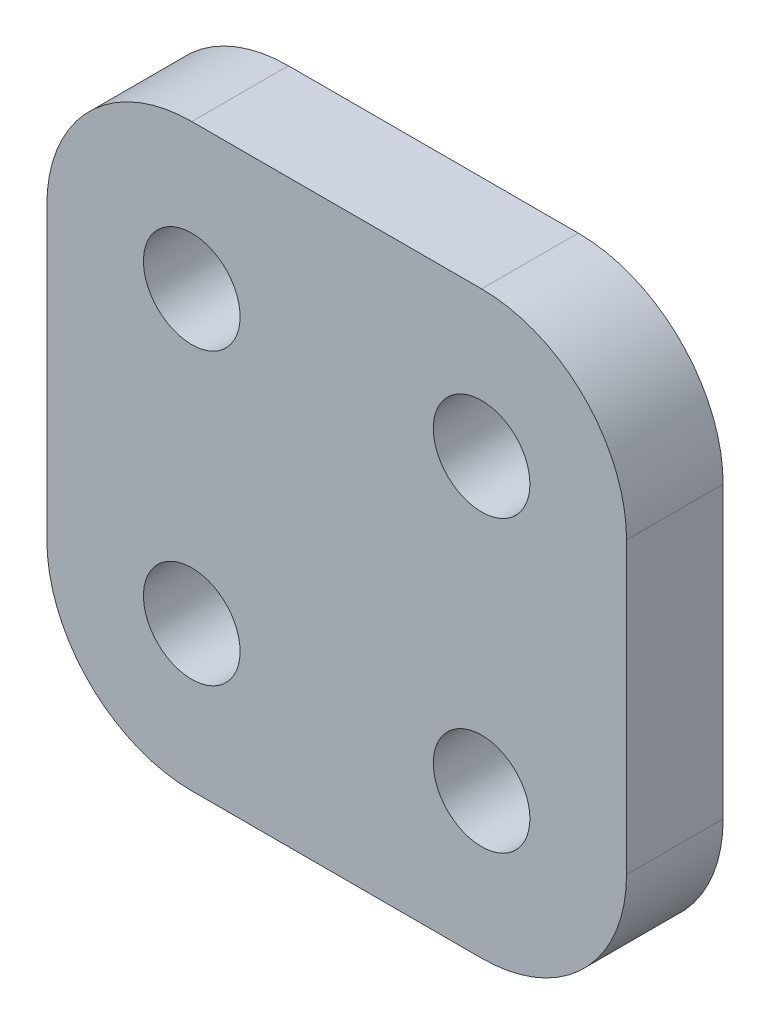
SolidWorks part; units mm, degrees
ref_plane "Alzado" through (0, 0, 0) normal (0, 0, 1) x (1, 0, 0)
ref_plane "Planta" through (0, 0, 0) normal (0, 1, 0) x (1, 0, 0)
ref_plane "Vista lateral" through (0, 0, 0) normal (1, 0, 0) x (0, 0, -1)
sketch "Model" plane through (0, 0, 0) normal (0, 0, 1) x (1, 0, 0)
  line L0 (195.3359, 161.3332) -> (204.3359, 161.3332)
  line L1 (208.8359, 165.8332) -> (208.8359, 174.8332)
  line L2 (204.3359, 179.3332) -> (195.3359, 179.3332)
  line L3 (190.8359, 174.8332) -> (190.8359, 165.8332)
  circle A0 centre (195.3359, 174.8332) radius 1.5
  circle A1 centre (195.3359, 165.8332) radius 1.5
  arc A2 (204.3359, 161.3332) -> (208.8359, 165.8332) centre (204.3359, 165.8332) ccw
  arc A3 (208.8359, 174.8332) -> (204.3359, 179.3332) centre (204.3359, 174.8332) ccw
  arc A4 (195.3359, 179.3332) -> (190.8359, 174.8332) centre (195.3359, 174.8332) ccw
  arc A5 (190.8359, 165.8332) -> (195.3359, 161.3332) centre (195.3359, 165.8332) ccw
  circle A6 centre (204.3359, 174.8332) radius 1.5
  circle A7 centre (204.3359, 165.8332) radius 1.5
extrude "Saliente-Extruir1" add sketch "Model" along normal blind 3
